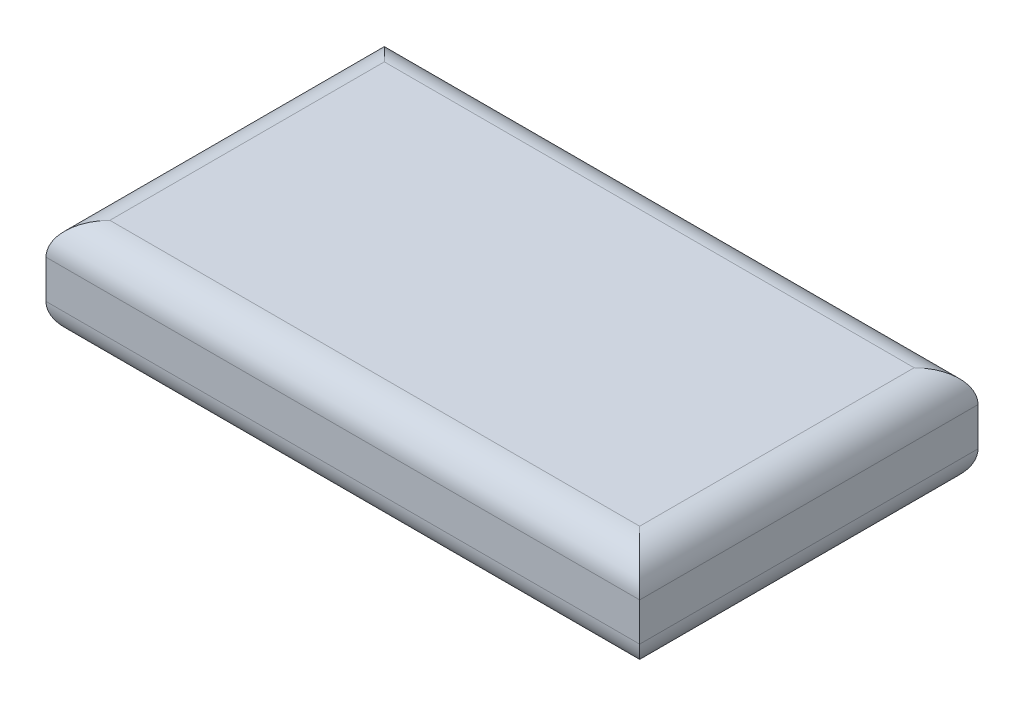
SolidWorks part; units mm, degrees
ref_plane "Front Plane" through (0, 0, 0) normal (0, 0, 1) x (1, 0, 0)
ref_plane "Top Plane" through (0, 0, 0) normal (0, 1, 0) x (1, 0, 0)
ref_plane "Right Plane" through (0, 0, 0) normal (1, 0, 0) x (0, 0, -1)
sketch "Sketch1" plane through (0, 0, 0) normal (0, 1, 0) x (1, 0, 0)
  line L1 (-23.25, -13.25) -> (23.25, -13.25)
  line L2 (-23.25, -13.25) -> (-23.25, 13.25)
  line L3 (-23.25, 13.25) -> (23.25, 13.25)
  line L4 (23.25, -13.25) -> (23.25, 13.25)
  line L5 (-23.25, -13.25) -> (23.25, 13.25) construction
  line L6 (-23.25, 13.25) -> (23.25, -13.25) construction
  point P0 (0, 0)
  dimension "D1" = 46.5
  dimension "D2" = 26.5
extrude "Boss-Extrude1" add sketch "Sketch1" along normal blind 8
fillet "Fillet1" radius 2.5 8 edges at (-23.25, 0, 0) (0, 0, 13.25) (23.25, 0, 0) (0, 0, -13.25) (23.25, 8, 0) (0, 8, -13.25) (-23.25, 8, 0) (0, 8, 13.25)
